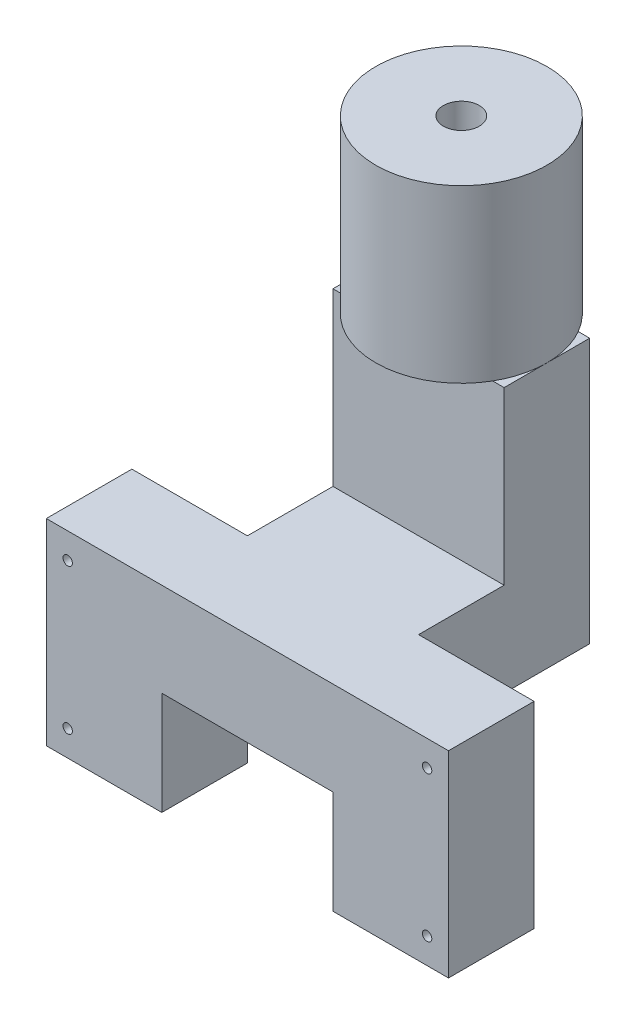
SolidWorks part; units mm, degrees
ref_plane "Front Plane" through (0, 0, 0) normal (0, 0, 1) x (1, 0, 0)
ref_plane "Top Plane" through (0, 0, 0) normal (0, 1, 0) x (1, 0, 0)
ref_plane "Right Plane" through (0, 0, 0) normal (1, 0, 0) x (0, 0, -1)
sketch "Esquisse1" plane through (0, 0, 0) normal (0, 0, 1) x (1, 0, 0)
  line L1 (-23.5, 11.5) -> (23.5, 11.5)
  line L2 (-23.5, 11.5) -> (-23.5, -11.5)
  line L3 (-23.5, -11.5) -> (23.5, -11.5)
  line L4 (23.5, 11.5) -> (23.5, -11.5)
  line L5 (-23.5, 11.5) -> (23.5, -11.5) construction
  line L6 (-23.5, -11.5) -> (23.5, 11.5) construction
  point P0 (0, 0)
  dimension "D1" = 47
  dimension "D2" = 23
extrude "Boss.-Extru.1" add sketch "Esquisse1" along normal blind 10
sketch "Esquisse2" plane through (0, 0, 10) normal (0, 0, 1) x (1, 0, 0)
  line L0 (-21, 8.5) -> (21, 8.5) construction
  line L1 (-22.5, 10) -> (22.5, 10) construction
  line L2 (-22.5, 10) -> (-22.5, -10) construction
  line L3 (-22.5, -10) -> (22.5, -10) construction
  line L4 (22.5, 10) -> (22.5, -10) construction
  line L5 (-22.5, 10) -> (22.5, -10) construction
  line L6 (-22.5, -10) -> (22.5, 10) construction
  line L7 (21, 8.5) -> (21, -8.5) construction
  line L8 (-21, -8.5) -> (21, -8.5) construction
  line L9 (-21, 8.5) -> (-21, -8.5) construction
  point P0 (0, 0)
  point P7 (-22.5, 10)
  point P8 (-22.5, -10)
  point P9 (22.5, 10)
  point P10 (22.5, -10)
  dimension "D1" = 45
  dimension "D2" = 20
  dimension "D3" = 1.5
hole_wizard "Trou taraudé M1.4x0.32" positions "Esquisse3D2" profile "Esquisse4" tap size "M1.4x0.3" standard "Ansi Metric" end condition through all
sketch3d "Esquisse3D2"
  point P0 (-21, 8.5, 10)
  point P3 (-21, -8.5, 10)
  point P6 (21, -8.5, 10)
  point P9 (21, 8.5, 10)
sketch "Esquisse4" plane through (-21, 8.5, 10) normal (1, 0, 0) x (0, -1, 0)
  line L0 (0, 0) -> (0, 10)
  line L1 (0, 10) -> (0.55, 10)
  line L2 (0.55, 10) -> (0.55, 0)
  line L5 (0.55, 0) -> (0, 0)
  line L11 (0, -6.35) -> (0, 107.95) construction
  dimension "Diamètre du trou pour taraudage jusqu'au prochain" = 1.1
  dimension "Profondeur du trou pour taraudage jusqu'au prochain" = 10
cosmetic thread "Filetage de perçage5" parameters "D2"=1.4
cosmetic thread "Filetage de perçage6" parameters "D2"=1.4
cosmetic thread "Filetage de perçage7" parameters "D2"=1.4
cosmetic thread "Filetage de perçage8" parameters "D2"=1.4
sketch "Esquisse5" plane through (0, 0, 10) normal (0, 0, 1) x (1, 0, 0)
  line L0 (0, 11.5) -> (0, -12.8034) construction
  line L1 (23.5, 11.5) -> (-23.5, 11.5) construction
  line L3 (-10, 0.5726) -> (10, 0.5726)
  line L4 (-10, 0.5726) -> (-10, -14.4274)
  line L5 (-10, -14.4274) -> (10, -14.4274)
  line L6 (10, 0.5726) -> (10, -14.4274)
  line L7 (-10, 0.5726) -> (10, -14.4274) construction
  line L8 (-10, -14.4274) -> (10, 0.5726) construction
  point P5 (0, -6.9274)
  dimension "D1" = 15
  dimension "D2" = 20
extrude "Enlèv. mat.-Extru.1" cut sketch "Esquisse5" against normal up to surface (10 mm away) up to face at (-20.45, 8.5, 0)
sketch "Esquisse6" plane through (0, 0, 0) normal (0, 0, -1) x (-1, 0, 0)
  line L0 (-23.5, 11.5) -> (23.5, 11.5) construction
  line L1 (-10, 0.5726) -> (10, 0.5726)
  line L2 (-10, 0.5726) -> (-10, 11.5)
  line L3 (-10, 11.5) -> (10, 11.5)
  line L4 (10, 0.5726) -> (10, 11.5)
extrude "Boss.-Extru.2" add sketch "Esquisse6" along normal blind 20
sketch "Esquisse9" plane through (0, 11.5, 0) normal (0, 1, 0) x (1, 0, 0)
  line L0 (10, 20) -> (10, 0) construction
  line L1 (-10, 20) -> (10, 20)
  line L2 (-10, 20) -> (-10, 10)
  line L3 (-10, 10) -> (10, 10)
  line L4 (10, 20) -> (10, 10)
  dimension "D1" = 10
extrude "Boss.-Extru.5" add sketch "Esquisse9" along normal blind 20
sketch "Esquisse10" plane through (0, 31.5, 0) normal (0, 1, 0) x (1, 0, 0)
  circle A0 centre (0, 15) radius 10
  dimension "D1" = 20
extrude "Boss.-Extru.6" add sketch "Esquisse10" along normal blind 20
hole_wizard "Trou taraudé M5x0.81" positions "Esquisse3D3" profile "Esquisse12" tap size "M5x0.8" standard "Ansi Metric"
sketch3d "Esquisse3D3"
  line L0 (0, 51.5, -15) -> (0, 31.5, -15) construction
  point P0 (0, 51.5, -15)
cosmetic thread "Filetage de perçage9" parameters "D1"=50.927, "D2"=5
sketch "Esquisse12" plane through (0, 51.5, -15) normal (1, 0, 0) x (0, 0, 1)
  line L0 (0, 0) -> (0, 11.2618)
  line L1 (0, 11.2618) -> (2.1, 10)
  line L2 (2.1, 10) -> (2.1, 0)
  line L5 (2.1, 0) -> (0, 0)
  line L10 (0, 11.2618) -> (-2.1, 10) construction
  line L11 (0, -6.35) -> (0, 107.95) construction
  dimension "Diamètre du trou pour taraudage" = 4.2
  dimension "Profondeur du trou pour taraudage" = 10
  dimension "Angle de pointe" = 118
